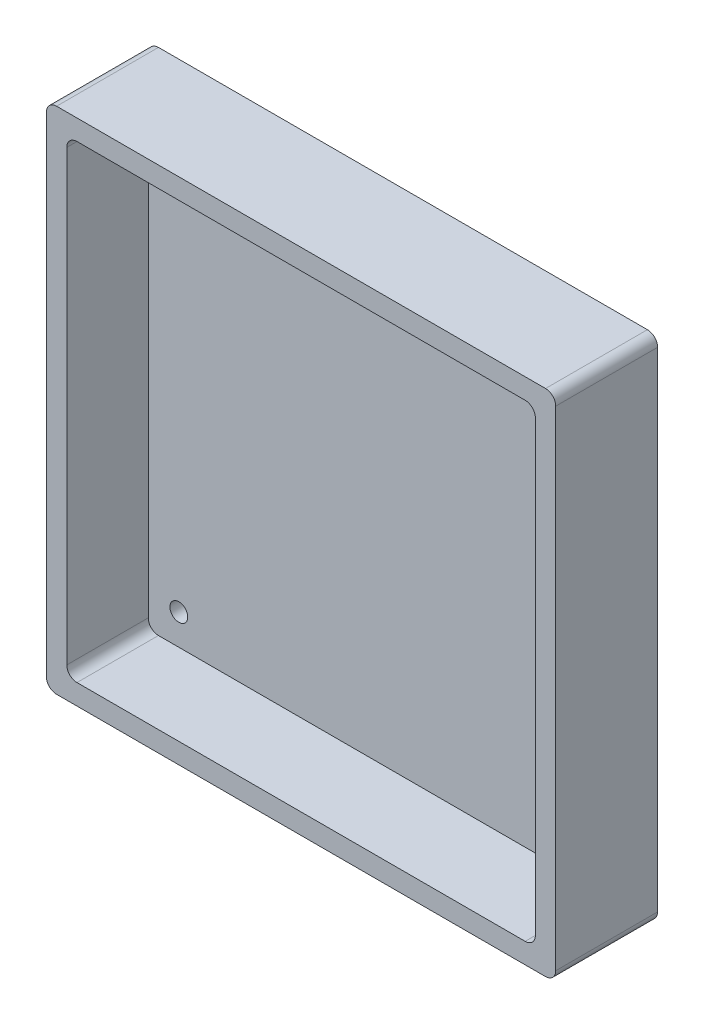
SolidWorks part; units mm, degrees
ref_plane "Front Plane" through (0, 0, 0) normal (0, 0, 1) x (1, 0, 0)
ref_plane "Top Plane" through (0, 0, 0) normal (0, 1, 0) x (1, 0, 0)
ref_plane "Right Plane" through (0, 0, 0) normal (1, 0, 0) x (0, 0, -1)
sketch "Sketch1" plane through (0, 0, 0) normal (0, 0, 1) x (1, 0, 0)
  line L1 (50, 50) -> (-50, 50)
  line L2 (50, 50) -> (50, -50)
  line L3 (50, -50) -> (-50, -50)
  line L4 (-50, 50) -> (-50, -50)
  line L5 (50, 50) -> (-50, -50) construction
  line L6 (50, -50) -> (-50, 50) construction
  point P0 (0, 0)
  dimension "D1" = 100
  dimension "D2" = 100
extrude "Boss-Extrude1" add sketch "Sketch1" along normal blind 20
ref_plane "Plane1" through (0, 0, 20) normal (0, 0, 1) x (1, 0, 0)
sketch "Sketch2" plane through (0, 0, 20) normal (0, 0, 1) x (1, 0, 0)
  line L1 (46, -46) -> (-46, -46)
  line L2 (46, -46) -> (46, 46)
  line L3 (46, 46) -> (-46, 46)
  line L4 (-46, -46) -> (-46, 46)
  line L5 (46, -46) -> (-46, 46) construction
  line L6 (46, 46) -> (-46, -46) construction
  point P0 (0, 0)
  dimension "D1" = 92
  dimension "D2" = 92
extrude "Cut-Extrude1" cut sketch "Sketch2" against normal blind 16
fillet "Fillet1" radius 2 8 edges at (-46, 46, 12) (46, 46, 12) (46, -46, 12) (-46, -46, 12) (50, -50, 10) (-50, -50, 10) (-50, 50, 10) (50, 50, 10)
sketch "Sketch3" plane through (0, 0, 0) normal (0, 0, 1) x (1, 0, 0)
  circle A1 centre (-40, 40) radius 1.75
  circle A2 centre (40, 40) radius 1.75
  circle A3 centre (40, -40) radius 1.75
  circle A4 centre (-40, -40) radius 1.75
  dimension "D1" = 3.5
  dimension "D4" = 4
extrude "Cut-Extrude2" cut sketch "Sketch3" along normal blind 16
